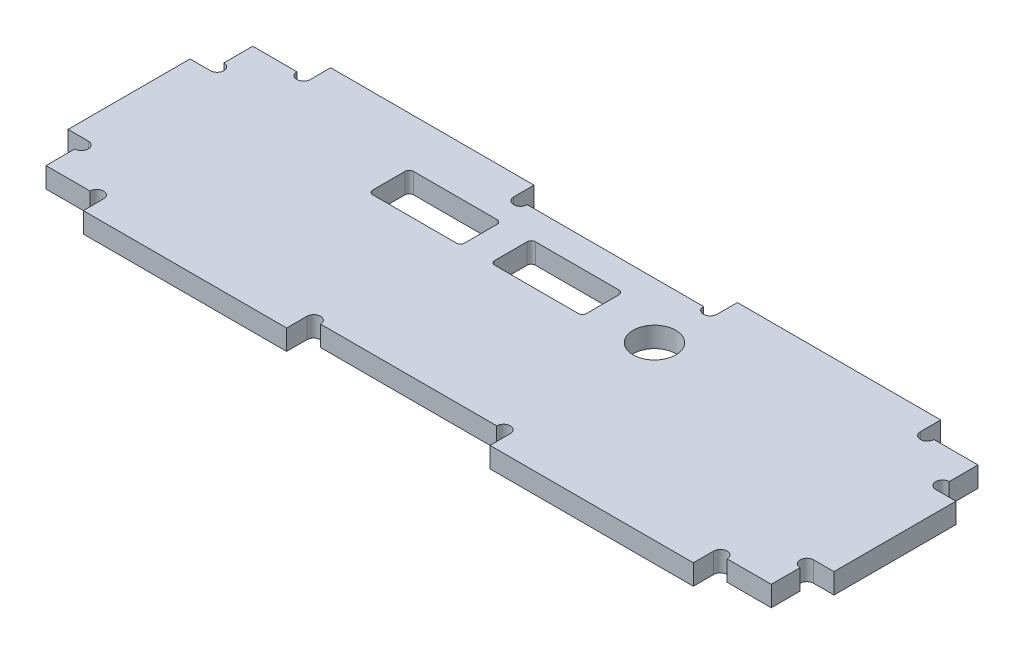
SolidWorks part; units mm, degrees
material "轻木"
ref_plane "Front" through (0, 0, 0) normal (0, 0, 1) x (1, 0, 0)
ref_plane "Top" through (0, 0, 0) normal (0, 1, 0) x (1, 0, 0)
ref_plane "Right" through (0, 0, 0) normal (1, 0, 0) x (0, 0, -1)
sketch "草图2" plane through (0, 0, 0) normal (0, 1, 0) x (1, 0, 0)
  line L0 (-49.5, 26.6) -> (-49.5, -15.2)
  line L1 (-49.5, -15.2) -> (49.5, -15.2)
  line L2 (49.5, 26.6) -> (49.5, -15.2)
  line L3 (49.5, 26.6) -> (-49.5, 26.6)
  line L4 (34.5, 2.85) -> (-34.5, 2.85)
  line L5 (-36.15, 4.5) -> (-36.15, 13.5)
  line L6 (-34.5, 15.15) -> (34.5, 15.15)
  line L7 (36.15, 13.5) -> (36.15, 4.5)
  arc A0 (34.5, 2.85) -> (36.15, 4.5) centre (34.5, 4.5) ccw
  arc A1 (-36.15, 4.5) -> (-34.5, 2.85) centre (-34.5, 4.5) ccw
  arc A2 (-34.5, 15.15) -> (-36.15, 13.5) centre (-34.5, 13.5) ccw
  arc A3 (36.15, 13.5) -> (34.5, 15.15) centre (34.5, 13.5) ccw
  dimension "D1" = 99
  dimension "D2" = 41.8
extrude "凸台-拉伸1" add sketch "草图2" along normal mid plane 3 contours L0 L1 L2 L3
sketch "草图3" plane through (0, 0, 0) normal (0, 1, 0) x (1, 0, 0)
  line L0 (36, 13.5) -> (36, 4.5)
  line L1 (-34.5, 15) -> (34.5, 15)
  line L2 (-36, 4.5) -> (-36, 13.5)
  line L3 (34.5, 3) -> (-34.5, 3)
  line L4 (5.275, 10.57) -> (5.275, 5.77)
  line L5 (4.675, 5.17) -> (-7.675, 5.17)
  line L6 (-8.275, 5.77) -> (-8.275, 10.57)
  line L7 (-7.675, 11.17) -> (4.675, 11.17)
  line L8 (-13.325, 5.17) -> (-25.675, 5.17)
  line L9 (-26.275, 5.77) -> (-26.275, 10.57)
  line L10 (-25.675, 11.17) -> (-13.325, 11.17)
  line L11 (-12.725, 10.57) -> (-12.725, 5.77)
  line L12 (49.5, 26.6) -> (-49.5, 26.6) construction
  arc A0 (36, 13.5) -> (34.5, 15) centre (34.5, 13.5) ccw
  arc A1 (-34.5, 15) -> (-36, 13.5) centre (-34.5, 13.5) ccw
  arc A2 (-36, 4.5) -> (-34.5, 3) centre (-34.5, 4.5) ccw
  arc A3 (34.5, 3) -> (36, 4.5) centre (34.5, 4.5) ccw
  circle A4 centre (14, 7.07) radius 3.15
  arc A5 (5.275, 10.57) -> (4.675, 11.17) centre (4.675, 10.57) ccw
  arc A6 (4.675, 5.17) -> (5.275, 5.77) centre (4.675, 5.77) ccw
  arc A7 (-8.275, 5.77) -> (-7.675, 5.17) centre (-7.675, 5.77) ccw
  arc A8 (-7.675, 11.17) -> (-8.275, 10.57) centre (-7.675, 10.57) ccw
  arc A9 (-13.325, 5.17) -> (-12.725, 5.77) centre (-13.325, 5.77) ccw
  arc A10 (-26.275, 5.77) -> (-25.675, 5.17) centre (-25.675, 5.77) ccw
  arc A11 (-25.675, 11.17) -> (-26.275, 10.57) centre (-25.675, 10.57) ccw
  arc A12 (-12.725, 10.57) -> (-13.325, 11.17) centre (-13.325, 10.57) ccw
  dimension "D1" = 19.53
extrude "切除-拉伸2" cut sketch "草图3" along normal mid plane 3 contours L10 A12 L11 A9 L8 A10 L9 A11 | L7 A5 L4 A6 L5 A7 L6 A8 | A4
sketch "草图5" plane through (0, -1.5, 0) normal (0, -1, 0) x (1, 0, 0)
  line L0 (49.5, -26.6) -> (49.5, 15.2) construction
  line L1 (-49.5, -26.6) -> (49.5, -26.6)
  line L2 (-49.5, -26.6) -> (-49.5, -15.3)
  line L3 (-49.5, -15.3) -> (49.5, -15.3)
  line L4 (49.5, -26.6) -> (49.5, -15.3)
  line L5 (-49.5, -26.6) -> (49.5, -15.3) construction
  line L6 (-49.5, -15.3) -> (49.5, -26.6) construction
  point P4 (0, -20.95)
  dimension "D1" = 11.3
extrude "切除-拉伸4" cut sketch "草图5" against normal blind 10
sketch "草图6" plane through (0, 0, 15.2) normal (0, 0, 1) x (1, 0, 0)
  line L0 (0, 1.5) -> (0, -10.5065) construction
  line L1 (-49.5, 1.5) -> (49.5, 1.5) construction
  line L2 (45, 1.5) -> (15, 1.5)
  line L3 (-45, -1.5) -> (-15, -1.5)
  line L4 (-45, -1.5) -> (-45, 1.5)
  line L5 (-45, 1.5) -> (-15, 1.5)
  line L6 (-15, -1.5) -> (-15, 1.5)
  line L7 (-30, 1.5) -> (-30, -1.5) construction
  line L8 (-45, 0) -> (-15, 0) construction
  line L9 (15, -1.5) -> (15, 1.5)
  line L10 (45, -1.5) -> (15, -1.5)
  line L11 (45, -1.5) -> (45, 1.5)
  point P5 (-30, 0)
  dimension "D1" = 30
  dimension "D2" = 30
extrude "凸台-拉伸2" add sketch "草图6" along normal blind 3
ref_plane "基准面1" through (0, 0, -0.05) normal (0, 0, 1) x (1, 0, 0)
mirror "镜向1" about plane through (0, 0, -0.05) normal (0, 0, 1) of "凸台-拉伸2"
sketch "草图8" plane through (0, 1.5, 0) normal (0, 1, 0) x (1, 0, 0)
  line L0 (-51.5, 0.05) -> (-73.2243, 0.05) construction
  line L1 (-49.5, 15.3) -> (-53.5, 15.3)
  line L2 (-49.5, 15.3) -> (-49.5, -15.2)
  line L3 (-49.5, -15.2) -> (-53.5, -15.2)
  line L4 (-53.5, 15.3) -> (-53.5, -15.2)
  line L5 (-49.5, 15.3) -> (-53.5, -15.2) construction
  line L6 (-49.5, -15.2) -> (-53.5, 15.3) construction
  line L7 (0, 0) -> (0, 24.2191) construction
  line L8 (-56.5, -8.95) -> (-53.5, -8.95)
  line L9 (-56.5, -8.95) -> (-56.5, 9.05)
  line L10 (-56.5, 9.05) -> (-53.5, 9.05)
  line L11 (-53.5, -8.95) -> (-53.5, 9.05)
  line L12 (-55, 9.05) -> (-55, -8.95) construction
  line L13 (-56.5, 0.05) -> (-53.5, 0.05) construction
  line L14 (56.5, 0.05) -> (53.5, 0.05) construction
  line L15 (55, 9.05) -> (55, -8.95) construction
  line L16 (49.5, -15.2) -> (53.5, 15.3) construction
  line L17 (49.5, 15.3) -> (53.5, -15.2) construction
  line L18 (53.5, -8.95) -> (53.5, 9.05)
  line L19 (56.5, 9.05) -> (53.5, 9.05)
  line L20 (56.5, -8.95) -> (56.5, 9.05)
  line L21 (56.5, -8.95) -> (53.5, -8.95)
  line L22 (53.5, 15.3) -> (53.5, -15.2)
  line L23 (49.5, -15.2) -> (53.5, -15.2)
  line L24 (49.5, 15.3) -> (49.5, -15.2)
  line L25 (49.5, 15.3) -> (53.5, 15.3)
  point P4 (-51.5, 0.05)
  point P5 (-55, 0.05)
  point P30 (55, 0.05)
  point P31 (51.5, 0.05)
  line M12 (-49.5, 15.3) -> (-49.5, -15.2)
  line M26 (49.5, -15.2) -> (49.5, 15.3)
  dimension "D1" = 18
  dimension "D2" = 3
  dimension "D3" = 4
extrude "凸台-拉伸3" add sketch "草图8" against normal up to surface (3 mm away) contours L10 L9 L8 L4 | L1 L4 L3 M12 | L25 L23 L22 L18 M26 | L21 L20 L19 L18 up to face at (-19.5, -1.5, -8.17)
sketch "草图7" plane through (0, 1.5, 0) normal (0, 1, 0) x (1, 0, 0)
  line L0 (-15, 15.3) -> (15, 15.3) construction
  line L1 (45, 15.3) -> (53.5, 15.3) construction
  line L3 (-15, -15.2) -> (15, -15.2) construction
  line L4 (-53.5, -15.2) -> (-45, -15.2) construction
  line L5 (-53.5, 15.3) -> (-45, 15.3) construction
  line L6 (45, -15.2) -> (53.5, -15.2) construction
  line L7 (-53.5, 15.3) -> (-53.5, 9.05) construction
  line L8 (-53.5, -8.95) -> (-53.5, -15.2) construction
  line L9 (53.5, 15.3) -> (53.5, 9.05) construction
  line L10 (53.5, -8.95) -> (53.5, -15.2) construction
  circle A0 centre (-14, 15.3) radius 1
  circle A1 centre (14, 15.3) radius 1
  circle A2 centre (46, 15.3) radius 1
  circle A4 centre (14, -15.2) radius 1
  circle A5 centre (-14, -15.2) radius 1
  circle A6 centre (-46, -15.2) radius 1
  circle A7 centre (-46, 15.3) radius 1
  circle A8 centre (46, -15.2) radius 1
  circle A9 centre (-53.5, 10.05) radius 1
  circle A10 centre (-53.5, -9.95) radius 1
  circle A11 centre (53.5, 10.05) radius 1
  circle A12 centre (53.5, -9.95) radius 1
  dimension "D1" = 2
  dimension "D2" = 2
extrude "切除-拉伸5" cut sketch "草图7" against normal blind 3
